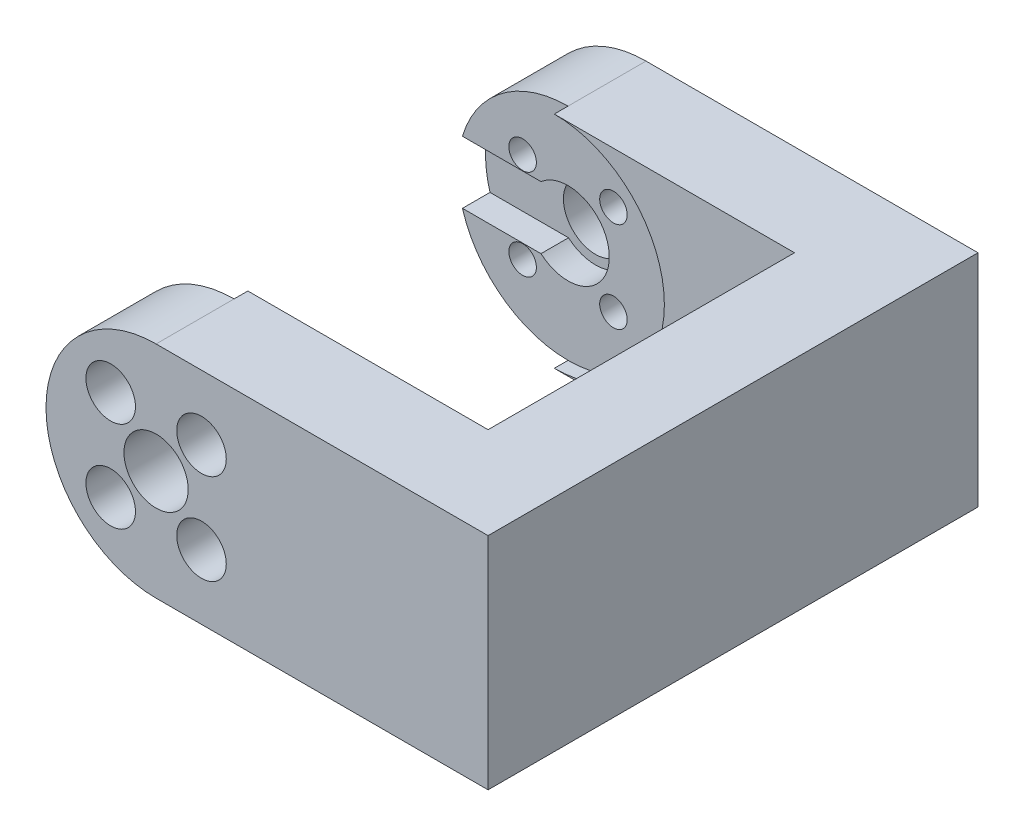
SolidWorks part; units mm, degrees
ref_plane "前视基准面" through (0, 0, 0) normal (0, 0, 1) x (1, 0, 0)
ref_plane "上视基准面" through (0, 0, 0) normal (0, 1, 0) x (1, 0, 0)
ref_plane "右视基准面" through (0, 0, 0) normal (1, 0, 0) x (0, 0, -1)
other "Configuration Table"
sketch "草图1" plane through (0, 0, 0) normal (0, 0, 1) x (1, 0, 0)
  line L0 (0, 12) -> (36.1853, 12)
  line L1 (36.1853, 12) -> (36.1853, -12)
  line L2 (36.1853, -12) -> (0, -12)
  arc A0 (0, 12) -> (0, -12) centre (0, 0) ccw
  dimension "D1" = 36.1853
extrude "凸台-拉伸1" add sketch "草图1" along normal blind 13.5
ref_plane "基准面1" through (0, 0, -16.7) normal (0, 0, -1) x (-1, 0, 0)
sketch "草图5" plane through (0, 0, 0) normal (0, 0, -1) x (-1, 0, 0)
  circle A0 centre (0, 0) radius 10.1
extrude "切除-拉伸2" cut sketch "草图5" against normal blind 1.5
sketch "草图7" plane through (0, 0, 1.5) normal (0, 0, -1) x (-1, 0, 0)
  circle A0 centre (0, 0) radius 3.5
extrude "切除-拉伸3" cut sketch "草图7" against normal blind 37
sketch "草图21" plane through (0, 0, 1.5) normal (0, 0, -1) x (-1, 0, 0)
  circle A0 centre (0, 0) radius 4.5
extrude "切除-拉伸12" cut sketch "草图21" against normal blind 3
sketch "草图9" plane through (0, 0, 1.5) normal (0, 0, -1) x (-1, 0, 0)
  line L0 (-4.9497, 4.9497) -> (0, 0) construction
  line L1 (0, 0) -> (0, 7.7766) construction
  circle A0 centre (-4.9497, 4.9497) radius 1.5
  circle A1 centre (4.9497, 4.9497) radius 1.5
  circle A2 centre (4.9497, -4.9497) radius 1.5
  circle A3 centre (-4.9497, -4.9497) radius 1.5
  point P14 (0, 0)
  dimension "D1" = 7
  dimension "D2" = 45
  dimension "D3" = 4
extrude "切除-拉伸4" cut sketch "草图9" against normal blind 24.5
mirror "镜向14" about plane through (0, 0, -16.7) normal (0, 0, -1) of bodies 111
sketch "草图11" plane through (36.1853, 0, 0) normal (1, 0, 0) x (0, 0, -1)
  line L1 (-13.5, 12) -> (46.9, 12)
  line L2 (-13.5, 12) -> (-13.5, -12)
  line L3 (-13.5, -12) -> (46.9, -12)
  line L4 (46.9, 12) -> (46.9, -12)
extrude "凸台-拉伸2" add sketch "草图11" against normal blind 10
sketch "草图12" plane through (0, 0, 13.5) normal (0, 0, 1) x (1, 0, 0)
  circle A0 centre (4.9497, 4.9497) radius 2.7
  circle A1 centre (4.9497, -4.9497) radius 2.7
  circle A2 centre (-4.9497, -4.9497) radius 2.7
  circle A3 centre (-4.9497, 4.9497) radius 2.7
  point P12 (0, 0)
  dimension "D1" = 4
extrude "切除-拉伸5" cut sketch "草图12" against normal blind 8.5
sketch "草图18" plane through (0, 0, 0) normal (0, 0, -1) x (-1, 0, 0)
  circle A0 centre (0, 0) radius 12
extrude "切除-拉伸9" cut sketch "草图18" against normal blind 1.5
sketch "草图19" plane through (0, 0, 1.5) normal (0, 0, -1) x (-1, 0, 0)
  line L4 (0, 0) -> (8.3144, 0) construction
  line L5 (16.6287, -3.4) -> (0, -3.4)
  line L6 (16.6287, -3.4) -> (16.6287, 3.4)
  line L7 (16.6287, 3.4) -> (0, 3.4)
  line L8 (0, -3.4) -> (0, 3.4)
  line L9 (16.6287, -3.4) -> (0, 3.4) construction
  line L10 (16.6287, 3.4) -> (0, -3.4) construction
  point P0 (8.3144, 0)
  dimension "D1" = 6.8
extrude "切除-拉伸10" cut sketch "草图19" against normal blind 3
sketch "草图20" plane through (0, 0, 13.5) normal (0, 0, 1) x (1, 0, 0)
  line L1 (-17.9701, 18.7991) -> (58.5374, 18.7991)
  line L2 (-17.9701, 18.7991) -> (-17.9701, -18.303)
  line L3 (-17.9701, -18.303) -> (58.5374, -18.303)
  line L4 (58.5374, 18.7991) -> (58.5374, -18.303)
extrude "切除-拉伸11" cut sketch "草图20" against normal blind 3.5
mirror "镜向24" about plane through (0, 0, -16.7) normal (0, 0, -1) of "切除-拉伸5", "切除-拉伸9", "切除-拉伸10"
mirror "镜向26" about plane through (0, 0, -16.7) normal (0, 0, -1) of "切除-拉伸11"
